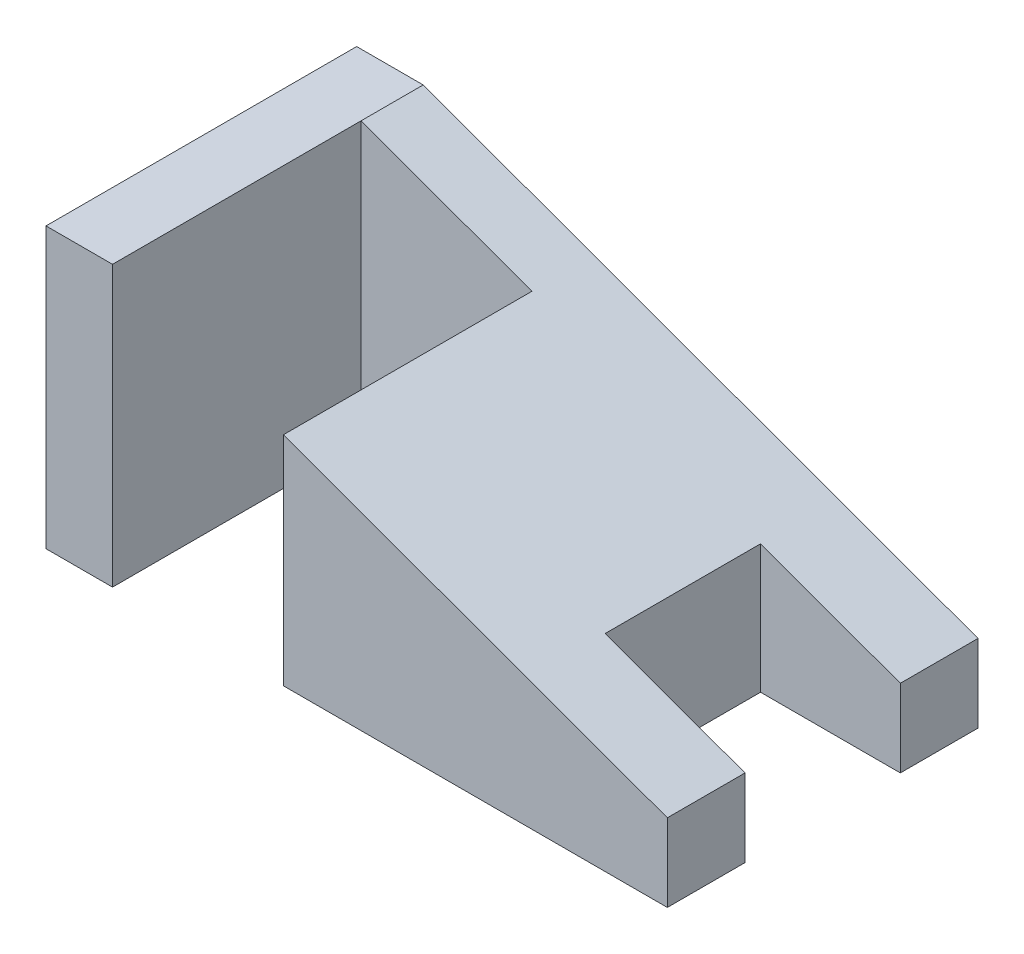
SolidWorks part; units mm, degrees
ref_plane "Front Plane" through (0, 0, 0) normal (0, 0, 1) x (1, 0, 0)
ref_plane "Top Plane" through (0, 0, 0) normal (0, 1, 0) x (1, 0, 0)
ref_plane "Right Plane" through (0, 0, 0) normal (1, 0, 0) x (0, 0, -1)
sketch "Sketch1" plane through (0, 0, 0) normal (0, 0, 1) x (1, 0, 0)
  line L0 (21.414, 0) -> (200, 0)
  line L1 (0, 0) -> (21.414, 0)
  line L2 (0, 0) -> (0, 90)
  line L3 (0, 90) -> (21.414, 90)
  line L4 (21.414, 0) -> (21.414, 90)
  line L5 (200, 0) -> (200, 25)
  line L6 (200, 25) -> (21.414, 90)
  dimension "D1" = 90
  dimension "D2" = 200
  dimension "D3" = 25
  dimension "D4" = 20
extrude "Boss-Extrude1" add sketch "Sketch1" along normal blind 100 contours L1 L4 L3 L2 | L5 L6 L4 L0
sketch "Sketch2" plane through (0, 90, 0) normal (0, 1, 0) x (1, 0, 0)
  line L0 (200, -50) -> (117.7855, -50) construction
  line L1 (21.414, -100) -> (76.414, -100)
  line L2 (21.414, -100) -> (21.414, -20)
  line L3 (21.414, -20) -> (76.414, -20)
  line L4 (76.414, -100) -> (76.414, -20)
  line L5 (200, -100) -> (200, 0) construction
  line L7 (200, -75) -> (155, -75)
  line L8 (200, -75) -> (200, -25)
  line L9 (200, -25) -> (155, -25)
  line L10 (155, -75) -> (155, -25)
  line M9 (21.414, -100) -> (21.414, 0)
  dimension "D1" = 55
  dimension "D2" = 80
  dimension "D3" = 45
  dimension "D4" = 50
extrude "Cut-Extrude1" cut sketch "Sketch2" against normal up to surface (90 mm away) contours L1 L4 L3 M9 | L0 L8 L9 L10 | L8 L0 L10 L7 up to face at (100, 0, 50)
